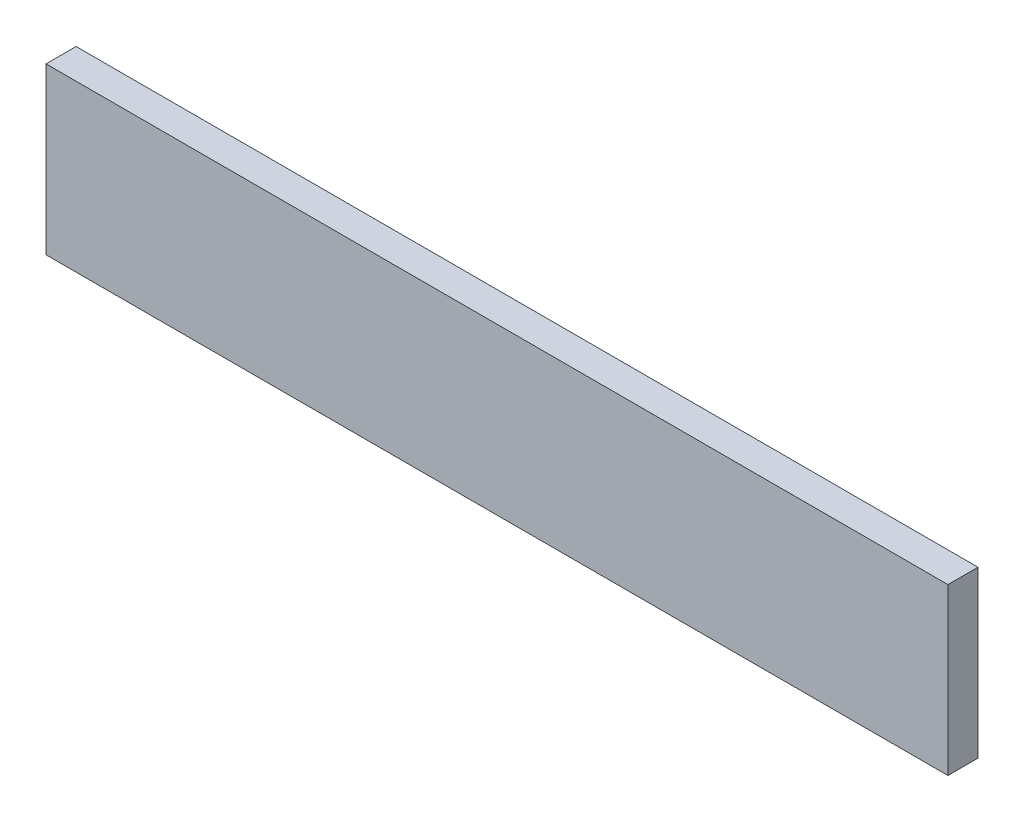
SolidWorks part; units mm, degrees
ref_plane "Front Plane" through (0, 0, 0) normal (0, 0, 1) x (1, 0, 0)
ref_plane "Top Plane" through (0, 0, 0) normal (0, 1, 0) x (1, 0, 0)
ref_plane "Right Plane" through (0, 0, 0) normal (1, 0, 0) x (0, 0, -1)
sketch "Sketch1" plane through (0, 0, 0) normal (0, 0, 1) x (1, 0, 0)
  line L1 (-95.25, -17.4625) -> (95.25, -17.4625)
  line L2 (-95.25, -17.4625) -> (-95.25, 17.4625)
  line L3 (-95.25, 17.4625) -> (95.25, 17.4625)
  line L4 (95.25, -17.4625) -> (95.25, 17.4625)
  line L5 (-95.25, -17.4625) -> (95.25, 17.4625) construction
  line L6 (-95.25, 17.4625) -> (95.25, -17.4625) construction
  point P0 (0, 0)
  dimension "D1" = 34.925
  dimension "D2" = 190.5
extrude "Boss-Extrude1" add sketch "Sketch1" along normal mid plane 6.35
